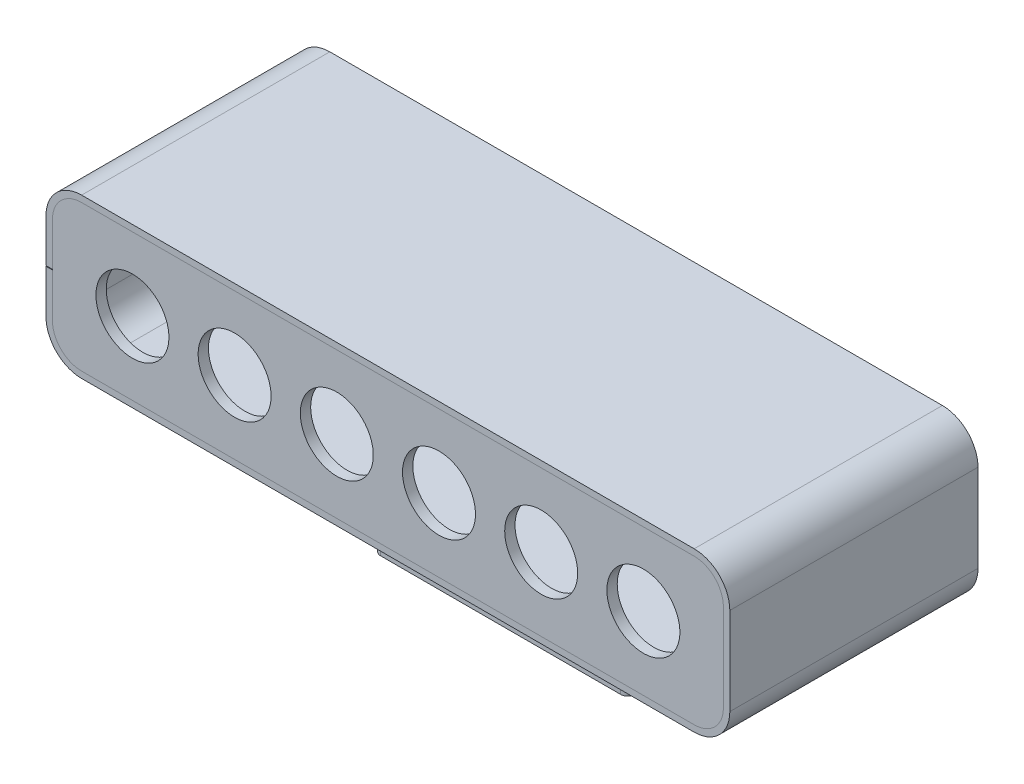
SolidWorks part; units mm, degrees
material "Acrylic (Medium-high impact)"
ref_plane "Front" through (0, 0, 0) normal (0, 0, 1) x (1, 0, 0)
ref_plane "Top" through (0, 0, 0) normal (0, 1, 0) x (1, 0, 0)
ref_plane "Right" through (0, 0, 0) normal (1, 0, 0) x (0, 0, -1)
sketch "Sketch5" plane through (0, 0, 0) normal (0, 1, 0) x (1, 0, 0)
  line L1 (0, 0) -> (-692.15, 0)
  line L2 (0, 0) -> (0, 107.95)
  line L3 (0, 107.95) -> (-692.15, 107.95)
  line L4 (-692.15, 0) -> (-692.15, 107.95)
  dimension "D1" = 107.95
  dimension "D2" = 692.15
extrude "Boss-Extrude4" [suppressed] add sketch "Sketch5" along normal blind 2.794
sketch "Sketch1" plane through (0, 0, 0) normal (0, 0, 1) x (1, 0, 0)
  line L1 (-145.923, 31.75) -> (145.923, 31.75)
  line L2 (-145.923, 31.75) -> (-145.923, -31.75)
  line L3 (-145.923, -31.75) -> (145.923, -31.75)
  line L4 (145.923, 31.75) -> (145.923, -31.75)
  line L5 (-145.923, 31.75) -> (145.923, -31.75) construction
  line L6 (-145.923, -31.75) -> (145.923, 31.75) construction
  point P0 (0, 0)
  dimension "D1" = 291.846
  dimension "D2" = 63.5
extrude "Boss-Extrude1" add sketch "Sketch1" along normal blind 4.4958
fillet "Fillet1" radius 12.7 4 edges at (-145.923, -31.75, 2.2479) (145.923, -31.75, 2.2479) (145.923, 31.75, 2.2479) (-145.923, 31.75, 2.2479)
sketch "Sketch3" plane through (0, 0, 0) normal (0, 0, 1) x (1, 0, 0)
  line L0 (133.223, 34.544) -> (-133.223, 34.544)
  line L1 (-148.717, 19.05) -> (-148.717, 0.254)
  line L2 (-133.223, -34.544) -> (133.223, -34.544)
  line L3 (148.717, -19.05) -> (148.717, 19.05)
  line L4 (-133.223, -31.75) -> (133.223, -31.75)
  line L5 (-145.923, 19.05) -> (-145.923, -19.05)
  line L6 (133.223, 31.75) -> (-133.223, 31.75)
  line L7 (145.923, -19.05) -> (145.923, 19.05)
  line L8 (-133.223, -31.75) -> (133.223, -31.75)
  line L9 (-145.923, 19.05) -> (-145.923, 0.254)
  line L10 (133.223, 31.75) -> (-133.223, 31.75)
  line L11 (145.923, -19.05) -> (145.923, 19.05)
  line L12 (-145.923, 0) -> (-148.717, 0)
  line L13 (-145.923, 0.254) -> (-148.717, 0.254)
  line L14 (-145.923, 0) -> (-145.923, -19.05)
  line L15 (-145.923, 19.05) -> (-145.923, -19.05) construction
  line L16 (-148.717, 0) -> (-148.717, -19.05)
  line L17 (-148.717, 19.05) -> (-148.717, -19.05) construction
  line L18 (-145.923, 19.05) -> (-145.923, -19.05) construction
  arc A0 (-133.223, 34.544) -> (-148.717, 19.05) centre (-133.223, 19.05) ccw
  arc A1 (-148.717, -19.05) -> (-133.223, -34.544) centre (-133.223, -19.05) ccw
  arc A2 (133.223, -34.544) -> (148.717, -19.05) centre (133.223, -19.05) ccw
  arc A3 (148.717, 19.05) -> (133.223, 34.544) centre (133.223, 19.05) ccw
  arc A4 (-145.923, -19.05) -> (-133.223, -31.75) centre (-133.223, -19.05) ccw
  arc A5 (-133.223, 31.75) -> (-145.923, 19.05) centre (-133.223, 19.05) ccw
  arc A6 (145.923, 19.05) -> (133.223, 31.75) centre (133.223, 19.05) ccw
  arc A7 (133.223, -31.75) -> (145.923, -19.05) centre (133.223, -19.05) ccw
  arc A8 (-145.923, -19.05) -> (-133.223, -31.75) centre (-133.223, -19.05) ccw
  arc A9 (-133.223, 31.75) -> (-145.923, 19.05) centre (-133.223, 19.05) ccw
  arc A10 (145.923, 19.05) -> (133.223, 31.75) centre (133.223, 19.05) ccw
  arc A11 (133.223, -31.75) -> (145.923, -19.05) centre (133.223, -19.05) ccw
  dimension "D3" = 0.254
  dimension "D1" = 0
  dimension "D2" = 2.794
extrude "Boss-Extrude2" add sketch "Sketch3" along normal blind 107.95 separate body
sketch "Sketch4" plane through (0, 0, 107.95) normal (0, 0, 1) x (1, 0, 0)
  line L4 (-145.923, 19.05) -> (-145.923, -19.05)
  line L5 (-133.223, -31.75) -> (133.223, -31.75)
  line L6 (145.923, -19.05) -> (145.923, 19.05)
  line L7 (133.223, 31.75) -> (-133.223, 31.75)
  line L8 (-145.923, 19.05) -> (-145.923, -19.05)
  line L9 (-133.223, -31.75) -> (133.223, -31.75)
  line L10 (145.923, -19.05) -> (145.923, 19.05)
  line L11 (133.223, 31.75) -> (-133.223, 31.75)
  arc A4 (-145.923, -19.05) -> (-133.223, -31.75) centre (-133.223, -19.05) ccw
  arc A5 (133.223, -31.75) -> (145.923, -19.05) centre (133.223, -19.05) ccw
  arc A6 (145.923, 19.05) -> (133.223, 31.75) centre (133.223, 19.05) ccw
  arc A7 (-133.223, 31.75) -> (-145.923, 19.05) centre (-133.223, 19.05) ccw
  arc A8 (-145.923, -19.05) -> (-133.223, -31.75) centre (-133.223, -19.05) ccw
  arc A9 (133.223, -31.75) -> (145.923, -19.05) centre (133.223, -19.05) ccw
  arc A10 (145.923, 19.05) -> (133.223, 31.75) centre (133.223, 19.05) ccw
  arc A11 (-133.223, 31.75) -> (-145.923, 19.05) centre (-133.223, 19.05) ccw
  dimension "D1" = 0
extrude "Boss-Extrude3" add sketch "Sketch4" against normal blind 4.4958 separate body
sketch "Sketch2" plane through (0, 0, 0) normal (0, 0, -1) x (-1, 0, 0)
  line L0 (22.225, 0) -> (-22.225, 0) construction
  line L1 (22.225, 0) -> (66.675, 0) construction
  line L2 (66.675, 0) -> (111.125, 0) construction
  line L3 (-22.225, 0) -> (-66.675, 0) construction
  line L4 (-66.675, 0) -> (-111.125, 0) construction
  line L5 (-111.125, 0) -> (-127, 0) construction
  line L6 (111.125, 0) -> (127, 0) construction
  circle A0 centre (-111.125, 0) radius 15.875
  circle A1 centre (-66.675, 0) radius 15.875
  circle A2 centre (-22.225, 0) radius 15.875
  circle A3 centre (22.225, 0) radius 15.875
  circle A4 centre (66.675, 0) radius 15.875
  circle A5 centre (111.125, 0) radius 15.875
  dimension "D1" = 31.75
  dimension "D2" = 254
extrude "Cut-Extrude1" cut sketch "Sketch2" against normal through all
sketch "Sketch6" plane through (0, -34.544, 0) normal (0, -1, 0) x (1, 0, 0)
  line L0 (0, 0) -> (0, 31.369) construction
  line L1 (-133.223, 0) -> (133.223, 0) construction
  line L2 (-52.705, 55.928) -> (-52.705, 6.81)
  line L3 (-52.245, 58.928) -> (52.245, 58.928)
  line L4 (-55.245, 55.928) -> (-55.245, 6.81)
  line L5 (-52.245, 3.81) -> (52.245, 3.81)
  line L6 (55.245, 55.928) -> (55.245, 6.81)
  line L7 (-55.245, 58.928) -> (55.245, 3.81) construction
  line L8 (-55.245, 3.81) -> (55.245, 58.928) construction
  line L9 (-52.245, 6.35) -> (52.245, 6.35)
  line L10 (52.705, 55.928) -> (52.705, 6.81)
  line L11 (-52.245, 56.388) -> (52.245, 56.388)
  arc A0 (-55.245, 6.81) -> (-52.245, 3.81) centre (-52.245, 6.81) ccw
  arc A1 (55.245, 6.81) -> (52.245, 3.81) centre (52.245, 6.81) cw
  arc A2 (55.245, 55.928) -> (52.245, 58.928) centre (52.245, 55.928) ccw
  arc A3 (-52.245, 58.928) -> (-55.245, 55.928) centre (-52.245, 55.928) ccw
  arc A4 (-52.705, 6.81) -> (-52.245, 6.35) centre (-52.245, 6.81) ccw
  arc A5 (52.705, 6.81) -> (52.245, 6.35) centre (52.245, 6.81) cw
  arc A6 (52.705, 55.928) -> (52.245, 56.388) centre (52.245, 55.928) ccw
  arc A7 (-52.245, 56.388) -> (-52.705, 55.928) centre (-52.245, 55.928) ccw
  dimension "D4" = 3
  dimension "D1" = 110.49
  dimension "D2" = 55.118
  dimension "D3" = 3.81
  dimension "D5" = 2.54
extrude "Boss-Extrude5" add sketch "Sketch6" along normal blind 50.8 separate body
sketch "Sketch7" plane through (0, 0, 0) normal (0, 0, -1) x (-1, 0, 0)
  line L0 (0, 0) -> (-52.3875, 0) construction
  line L1 (0, 0) -> (52.3875, 0) construction
  circle A0 centre (-52.3875, 0) radius 3.175
  circle A1 centre (52.3875, 0) radius 3.175
  dimension "D1" = 6.35
  dimension "D2" = 104.775
extrude "Cut-Extrude2" cut sketch "Sketch7" against normal up to next (4.4958 mm away)
sketch "Sketch8" plane through (0, -34.544, 0) normal (0, -1, 0) x (1, 0, 0)
  line L0 (0, 3.81) -> (0, 58.928) construction
  line L1 (-52.245, 3.81) -> (52.245, 3.81) construction
  line L2 (52.245, 58.928) -> (-52.245, 58.928) construction
  line L4 (-46.355, 53.594) -> (46.355, 53.594)
  line L5 (-50.165, 49.784) -> (-50.165, 12.954)
  line L6 (-46.355, 9.144) -> (46.355, 9.144)
  line L7 (50.165, 49.784) -> (50.165, 12.954)
  line L8 (-50.165, 53.594) -> (50.165, 9.144) construction
  line L9 (-50.165, 9.144) -> (50.165, 53.594) construction
  arc A0 (-50.165, 12.954) -> (-46.355, 9.144) centre (-46.355, 12.954) ccw
  arc A1 (50.165, 12.954) -> (46.355, 9.144) centre (46.355, 12.954) cw
  arc A2 (50.165, 49.784) -> (46.355, 53.594) centre (46.355, 49.784) ccw
  arc A3 (-46.355, 53.594) -> (-50.165, 49.784) centre (-46.355, 49.784) ccw
  point P6 (0, 31.369)
  dimension "D3" = 3.81
  dimension "D1" = 100.33
  dimension "D2" = 44.45
extrude "Cut-Extrude3" cut sketch "Sketch8" against normal up to next (2.794 mm away)
sketch "Sketch9" plane through (0, -34.544, 0) normal (0, -1, 0) x (1, 0, 0)
  line L1 (-120.717, 25) -> (-120.717, 0) construction
  line L5 (-133.223, 0) -> (133.223, 0) construction
  line L6 (-148.717, 107.95) -> (-148.717, 0) construction
  circle A0 centre (-120.717, 25) radius 15.875
  dimension "D1" = 31.75
  dimension "D2" = 25
  dimension "D3" = 28
extrude "Cut-Extrude4" cut sketch "Sketch9" along normal through all from surface at -66.294 starting at face at (0, 31.75, 53.975)
sketch "Sketch10" plane through (0, -34.544, 0) normal (0, -1, 0) x (1, 0, 0)
  circle A0 centre (63.5, 50.8) radius 1.7463
  circle A1 centre (63.5, 12.7) radius 1.7463
  circle A2 centre (-63.5, 50.8) radius 1.7462
  circle A3 centre (-63.5, 12.7) radius 1.7462
  arc A5 (-61.7042, 48.1817) -> (-60.3345, 51.046) centre (-63.5, 50.8) ccw construction
  arc A6 (-63.8073, 9.5399) -> (-60.9169, 10.8538) centre (-63.5, 12.7) ccw construction
  circle A7 centre (63.5, 50.8) radius 1.4732 construction
  circle A8 centre (63.5, 12.7) radius 1.4732 construction
  dimension "D1" = 3.4925
extrude "Cut-Extrude5" cut sketch "Sketch10" against normal up to next (2.794 mm away)
sketch "Sketch11" [suppressed] plane through (0, -31.75, 0) normal (0, 1, 0) x (1, 0, 0)
  line L0 (-133.223, -107.95) -> (-133.223, 0) construction
  line L1 (-133.223, -107.95) -> (-133.223, 0)
  line L2 (133.223, -107.95) -> (133.223, 0) construction
  line L3 (133.223, -107.95) -> (133.223, 0)
  line L4 (133.223, -107.95) -> (148.717, -107.95)
  line L5 (148.717, -107.95) -> (148.717, 0)
  line L6 (148.717, 0) -> (133.223, 0)
  line L7 (-133.223, 0) -> (-148.717, 0)
  line L8 (-148.717, 0) -> (-148.717, -107.95)
  line L9 (-148.717, -107.95) -> (-133.223, -107.95)
extrude "Cut-Extrude6" [suppressed] cut sketch "Sketch11" along normal through all
sketch "Sketch12" [suppressed] plane through (0, -31.75, 0) normal (0, 1, 0) x (1, 0, 0)
  line L0 (-133.223, -107.95) -> (-133.223, 0) construction
  line L1 (-133.223, -107.95) -> (-133.223, 0)
  line L2 (133.223, -107.95) -> (133.223, 0) construction
  line L3 (133.223, -107.95) -> (133.223, 0)
  line L4 (-142.0985, 0) -> (-142.0985, -107.95) construction
  line L5 (142.0985, 0) -> (-142.0985, 0) construction
  line L6 (142.0985, -107.95) -> (142.0985, 0) construction
  line L7 (142.0985, -107.95) -> (-142.0985, -107.95) construction
  line L8 (-142.0985, 0) -> (-142.0985, -107.95)
  line L9 (142.0985, 0) -> (133.223, 0)
  line L10 (142.0985, -107.95) -> (142.0985, 0)
  line L11 (142.0985, -107.95) -> (133.223, -107.95)
  line L12 (-133.223, -107.95) -> (-142.0985, -107.95)
  line L13 (-133.223, 0) -> (-142.0985, 0)
extrude "Cut-Extrude7" [suppressed] cut sketch "Sketch12" against normal through all
sketch "Sketch13" [suppressed] plane through (0, 34.544, 0) normal (0, 1, 0) x (1, 0, 0)
  line L4 (133.223, 0) -> (-133.223, 0)
  line L5 (-133.223, 0) -> (-133.223, -107.95)
  line L6 (-133.223, -107.95) -> (133.223, -107.95)
  line L7 (133.223, -107.95) -> (133.223, 0)
  line L8 (133.223, 0) -> (-133.223, 0)
  line L9 (-133.223, 0) -> (-133.223, -107.95)
  line L10 (-133.223, -107.95) -> (133.223, -107.95)
  line L11 (133.223, -107.95) -> (133.223, 0)
  dimension "D1" = 0
extrude "Cut-Extrude8" [suppressed] cut sketch "Sketch13" against normal up to surface (2.794 mm away)
sketch "Sketch14" [suppressed] plane through (0, -31.75, 0) normal (0, 1, 0) x (1, 0, 0)
  line L1 (-133.223, -107.95) -> (-171.323, -107.95)
  line L2 (-133.223, -107.95) -> (-133.223, 0)
  line L3 (-133.223, 0) -> (-171.323, 0)
  line L4 (-171.323, -107.95) -> (-171.323, 0)
  dimension "D1" = 38.1
sketch "Sketch15" [suppressed] plane through (0, -31.75, 0) normal (0, 1, 0) x (1, 0, 0)
  line L0 (-133.223, -107.95) -> (-133.223, 0) construction
  line L1 (133.223, -107.95) -> (558.927, -107.95)
  line L2 (133.223, -107.95) -> (133.223, 0)
  line L3 (133.223, 0) -> (558.927, 0)
  line L4 (558.927, -107.95) -> (558.927, 0)
  dimension "D1" = 692.15
extrude "Boss-Extrude6" [suppressed] add sketch "Sketch15" against normal up to surface (2.794 mm away)
